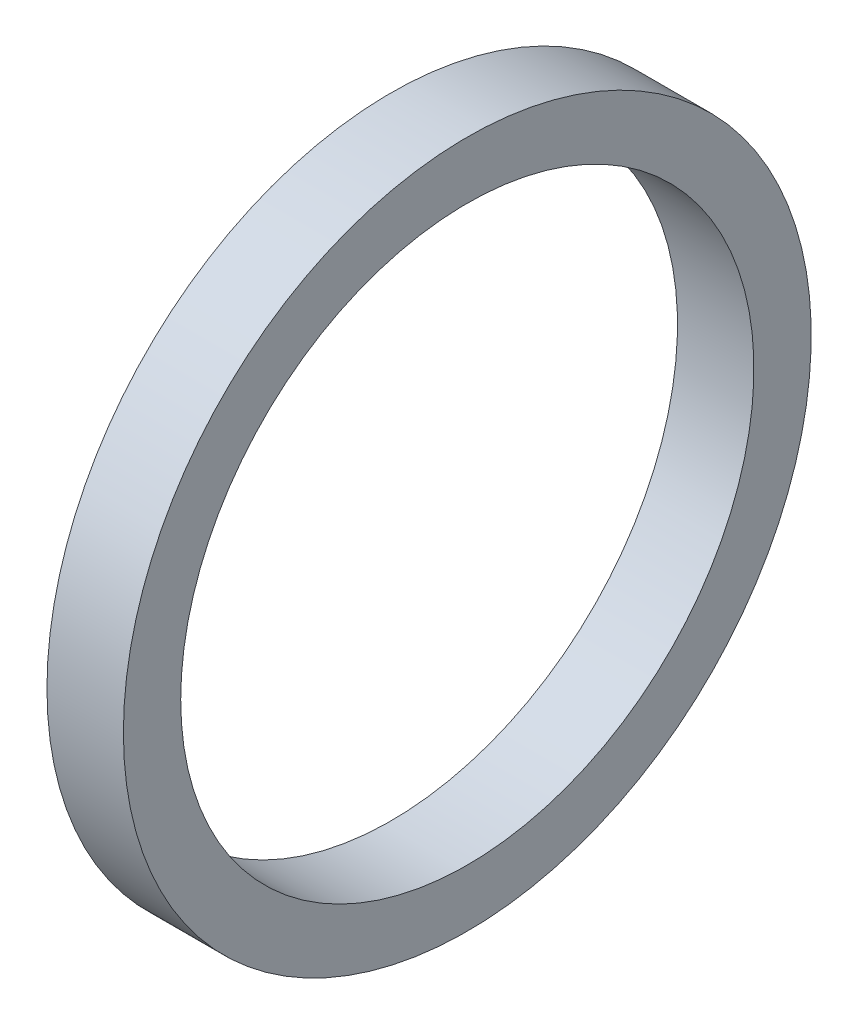
SolidWorks part; units mm, degrees
ref_plane "Alzado" through (0, 0, 0) normal (0, 0, 1) x (1, 0, 0)
ref_plane "Planta" through (0, 0, 0) normal (0, 1, 0) x (1, 0, 0)
ref_plane "Vista lateral" through (0, 0, 0) normal (1, 0, 0) x (0, 0, -1)
sketch "Croquis1" plane through (0, 0, 0) normal (0, 1, 0) x (1, 0, 0)
  line L0 (0, 0) -> (0, 7.5) construction
  line L1 (0, 7.5) -> (2, 7.5)
  line L2 (2, 7.5) -> (2, 9)
  line L3 (2, 9) -> (0, 9)
  line L4 (0, 9) -> (0, 8.75)
  line L7 (0, 7.75) -> (0, 7.5)
  line L10 (0, 0) -> (3.5179, 0) construction
  line L11 (0, 8.75) -> (1.3755, 8.4958)
  line L12 (1.3755, 8.0042) -> (0, 7.75)
  arc A1 (1.3755, 8.4958) -> (1.3755, 8.0042) centre (1.33, 8.25) cw
  dimension "D2" = 0.25
  dimension "D6" = 0.25
  dimension "D1" = 7.5
  dimension "D3" = 2
  dimension "D4" = 2
  dimension "D5" = 1.5
revolve "Revolución1" add sketch "Croquis1" angle 360 about L10
